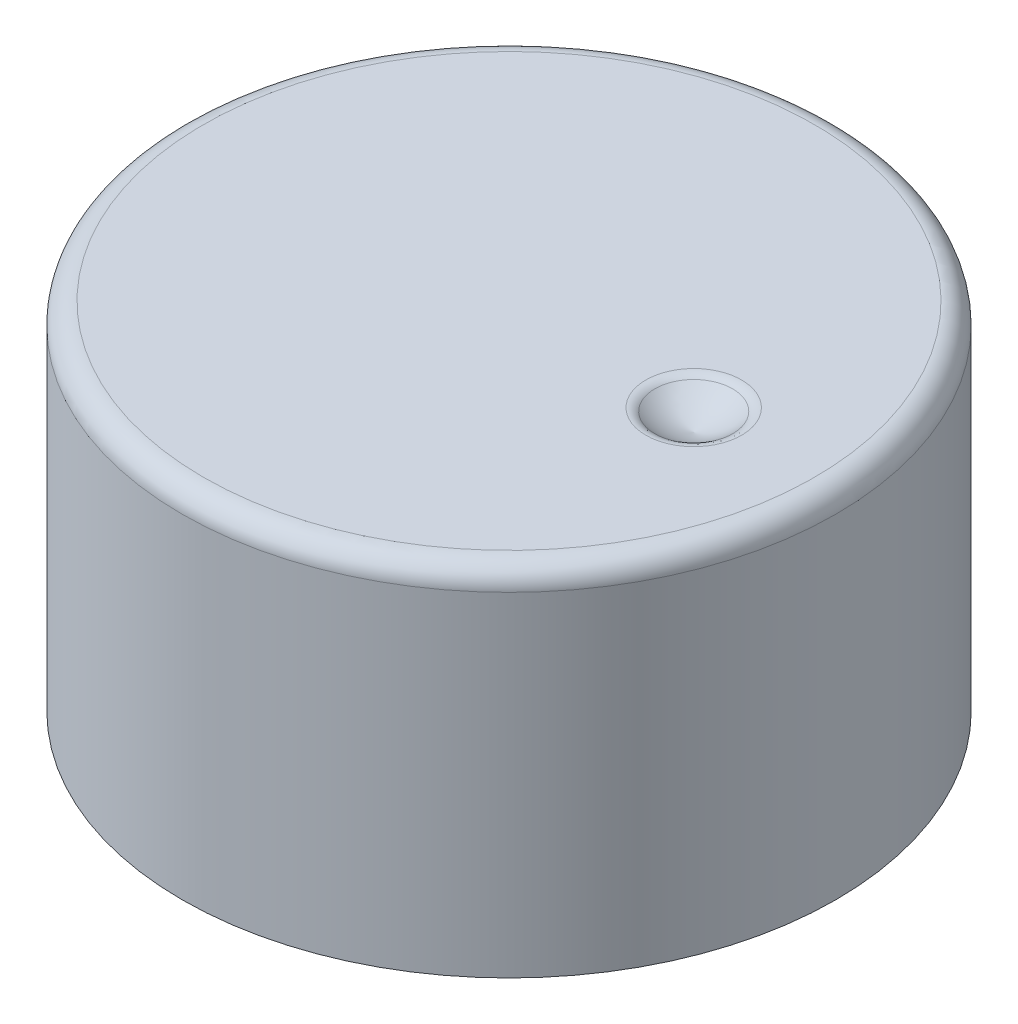
SolidWorks part; units mm, degrees
ref_plane "Front Plane" through (0, 0, 0) normal (0, 0, 1) x (1, 0, 0)
ref_plane "Top Plane" through (0, 0, 0) normal (0, 1, 0) x (1, 0, 0)
ref_plane "Right Plane" through (0, 0, 0) normal (1, 0, 0) x (0, 0, -1)
sketch "Sketch1" plane through (0, 0, 0) normal (0, 1, 0) x (1, 0, 0)
  circle A0 centre (0, 0) radius 23
  dimension "D1" = 46
extrude "Boss-Extrude1" add sketch "Sketch1" along normal blind 25
sketch "Sketch3" plane through (0, 0, 0) normal (0, -1, 0) x (-1, 0, 0)
  line L0 (-0.45, 3.0672) -> (-0.45, -3.0672)
  line L1 (0.45, 3.0672) -> (0.45, -3.0672)
  circle A0 centre (0, 0) radius 3.1
  dimension "D1" = 6.2
  dimension "D2" = 0.9
  dimension "D3" = 0.45
extrude "Cut-Extrude1" cut sketch "Sketch3" against normal blind 23 contours L0 A0 | L1 A0
sketch "Sketch4" plane through (0, 0, 0) normal (0, -1, 0) x (-1, 0, 0)
  circle A0 centre (0, 0) radius 10
  dimension "D1" = 20
extrude "Cut-Extrude2" cut sketch "Sketch4" against normal blind 12
chamfer "Chamfer1" distance 10 angle 50 1 edges at (0, 0, -10)
fillet "Fillet1" radius 1.5 1 edges at (0, 25, 23)
sketch "Sketch5" plane through (0, 0, 0) normal (0, 0, 1) x (1, 0, 0)
  line L0 (13, 25) -> (13, 23.5)
  line L1 (13, 25) -> (16, 25)
  line L2 (21.5, 25) -> (-21.5, 25) construction
  line L4 (-23, 23.5) -> (-23, 0) construction
  arc A0 (16, 25) -> (13, 23.5) centre (11.8371, 29.5757) cw
  dimension "D1" = 1.5
  dimension "D2" = 3
  dimension "D3" = 0
  dimension "D4" = 36
ref_axis "Axis1" through (13, 25, 0) along (0, -1, 0)
revolve "Cut-Revolve1" cut sketch "Sketch5" angle 360 about axis through (13, 25, 0) along (0, -1, 0)
fillet "Fillet2" radius 1 1 edges at (13, 25, 3)
